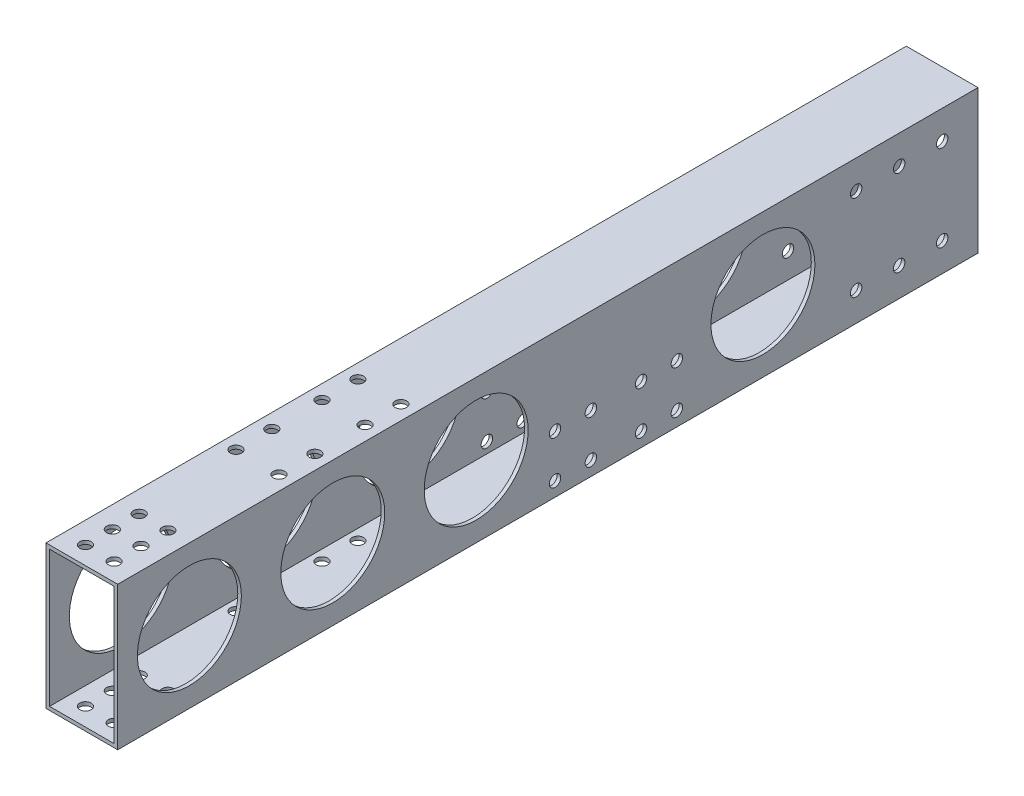
SolidWorks part; units mm, degrees
material "2014-T6"
ref_plane "前视基准面" through (0, 0, 0) normal (0, 0, 1) x (1, 0, 0)
ref_plane "上视基准面" through (0, 0, 0) normal (0, 1, 0) x (1, 0, 0)
ref_plane "右视基准面" through (0, 0, 0) normal (1, 0, 0) x (0, 0, -1)
other "Configuration Table"
sketch "草图1" plane through (0, 0, 0) normal (0, 0, 1) x (1, 0, 0)
  line L1 (0, 0) -> (20, 0)
  line L2 (0, 0) -> (0, 40)
  line L3 (0, 40) -> (20, 40)
  line L4 (20, 0) -> (20, 40)
  line L5 (1, 1) -> (19, 1)
  line L6 (1, 1) -> (1, 39)
  line L7 (1, 39) -> (19, 39)
  line L8 (19, 1) -> (19, 39)
  dimension "D1" = 20
  dimension "D2" = 40
  dimension "D3" = 1
  dimension "D4" = 1
  dimension "D5" = 1
  dimension "D6" = 1
extrude "凸台-拉伸1" add sketch "草图1" along normal blind 240
sketch "草图2" plane through (20, 0, 0) normal (1, 0, 0) x (0, 0, -1)
  circle A1 centre (-10, 8) radius 1.6
  circle A3 centre (-10, 8) radius 1.6
  circle A5 centre (-34, 8) radius 1.6
  circle A7 centre (-34, 8) radius 1.6
  circle A9 centre (-84, 4) radius 1.6
  circle A10 centre (-84, 4) radius 1.6
  circle A11 centre (-94, 4) radius 1.6
  circle A12 centre (-94, 4) radius 1.6
  circle A13 centre (-108, 16) radius 1.6
  circle A14 centre (-108, 16) radius 1.6
  circle A15 centre (-118, 16) radius 1.6
  circle A16 centre (-118, 16) radius 1.6
  circle A17 centre (-108, 4) radius 1.6
  circle A18 centre (-108, 4) radius 1.6
  circle A19 centre (-118, 4) radius 1.6
  circle A20 centre (-118, 4) radius 1.6
  circle A21 centre (-84, 16) radius 1.6
  circle A22 centre (-84, 16) radius 1.6
  circle A23 centre (-94, 16) radius 1.6
  circle A24 centre (-94, 16) radius 1.6
  circle A25 centre (-10, 32) radius 1.6
  circle A26 centre (-10, 32) radius 1.6
  circle A27 centre (-34, 32) radius 1.6
  circle A28 centre (-34, 32) radius 1.6
  circle A45 centre (-22, 32) radius 1.6
  circle A46 centre (-22, 32) radius 1.6
  circle A47 centre (-22, 8) radius 1.6
  circle A52 centre (-22, 8) radius 1.6
  dimension "D2" = 0
  dimension "D3" = 0
  dimension "D4" = 0
  dimension "D5" = 0
  dimension "D6" = 0
  dimension "D7" = 0
  dimension "D8" = 0
  dimension "D9" = 0
  dimension "D10" = 0
  dimension "D11" = 0
  dimension "D12" = 0
  dimension "D13" = 0
  dimension "D22" = 0
  dimension "D24" = 0
extrude "切除-拉伸1" cut sketch "草图2" against normal through all
sketch "草图3" plane through (0, 40, 0) normal (0, 1, 0) x (1, 0, 0)
  circle A1 centre (6, -227.5) radius 1.6
  circle A3 centre (6, -227.5) radius 1.6
  circle A5 centre (14, -227.5) radius 1.6
  circle A7 centre (14, -227.5) radius 1.6
  circle A9 centre (16, -191) radius 1.6
  circle A10 centre (16, -191) radius 1.6
  circle A11 centre (16, -181) radius 1.6
  circle A12 centre (16, -181) radius 1.6
  circle A13 centre (4, -167) radius 1.6
  circle A14 centre (4, -167) radius 1.6
  circle A15 centre (4, -157) radius 1.6
  circle A16 centre (4, -157) radius 1.6
  circle A17 centre (16, -167) radius 1.6
  circle A18 centre (16, -167) radius 1.6
  circle A19 centre (16, -157) radius 1.6
  circle A20 centre (16, -157) radius 1.6
  circle A21 centre (4, -191) radius 1.6
  circle A22 centre (4, -191) radius 1.6
  circle A23 centre (4, -181) radius 1.6
  circle A24 centre (4, -181) radius 1.6
  circle A25 centre (6, -220) radius 1.6
  circle A26 centre (6, -220) radius 1.6
  circle A27 centre (14, -220) radius 1.6
  circle A28 centre (14, -220) radius 1.6
  circle A29 centre (6, -235) radius 1.6
  circle A30 centre (6, -235) radius 1.6
  circle A31 centre (14, -235) radius 1.6
  circle A32 centre (14, -235) radius 1.6
  dimension "D2" = 0
  dimension "D3" = 0
  dimension "D4" = 0
  dimension "D5" = 0
  dimension "D6" = 0
  dimension "D7" = 0
  dimension "D8" = 0
  dimension "D9" = 0
  dimension "D10" = 0
  dimension "D11" = 0
  dimension "D12" = 0
  dimension "D13" = 0
  dimension "D14" = 0
  dimension "D15" = 0
extrude "切除-拉伸2" cut sketch "草图3" against normal through all
sketch "草图4" plane through (20, 0, 0) normal (1, 0, 0) x (0, 0, -1)
  line L1 (-228.7249, 20) -> (-179.2846, 20) construction
  line L2 (-240, 0) -> (-240, 40) construction
  line L3 (-240, 0) -> (0, 0) construction
  circle A0 centre (-220, 20) radius 14.5
  circle A1 centre (-180, 20) radius 14.5
  circle A2 centre (-140, 20) radius 14.5
  circle A3 centre (-100, 20) radius 14.5 [skipped]
  circle A4 centre (-60, 20) radius 14.5
  dimension "D1" = 29
  dimension "D2" = 20
  dimension "D3" = 20
  dimension "D5" = 40
  dimension "D4" = 5
extrude "切除-拉伸3" cut sketch "草图4" against normal through all
